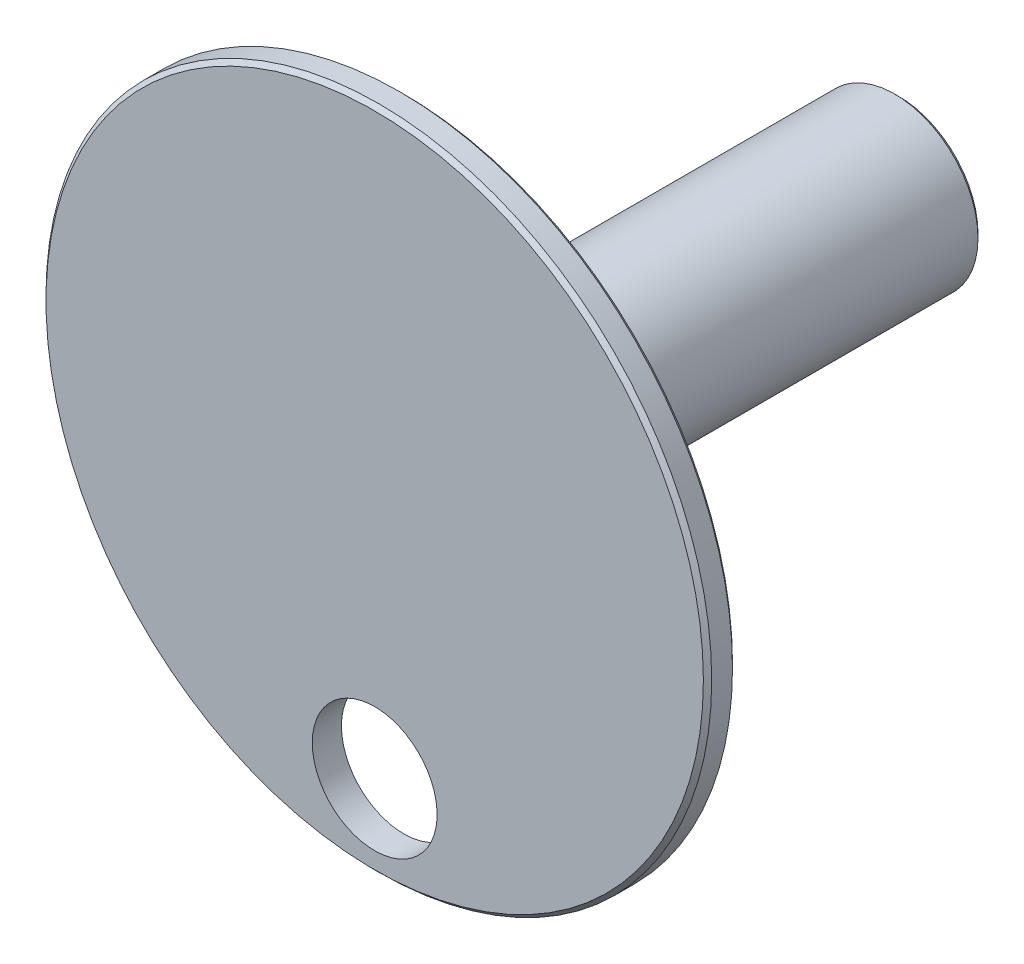
SolidWorks part; units mm, degrees
ref_plane "Front Plane" through (0, 0, 0) normal (0, 0, 1) x (1, 0, 0)
ref_plane "Top Plane" through (0, 0, 0) normal (0, 1, 0) x (1, 0, 0)
ref_plane "Right Plane" through (0, 0, 0) normal (1, 0, 0) x (0, 0, -1)
sketch "Sketch2" plane through (0, 0, 0) normal (0, 0, 1) x (1, 0, 0)
  circle A0 centre (0, 0) radius 2
  dimension "D1" = 4
extrude "Boss-Extrude1" add sketch "Sketch2" along normal blind 11.6
sketch "Sketch3" plane through (0, 0, 11.6) normal (0, 0, 1) x (1, 0, 0)
  circle A0 centre (0, 0) radius 4
  dimension "D1" = 8
extrude "Boss-Extrude2" add sketch "Sketch3" along normal blind 0.3
sketch "Sketch4" plane through (0, 0, 11.9) normal (0, 0, 1) x (1, 0, 0)
  circle A0 centre (0, 0) radius 8
  dimension "D1" = 16
extrude "Boss-Extrude3" add sketch "Sketch4" along normal blind 0.7
sketch "Sketch5" plane through (0, 0, 0) normal (0, 0, -1) x (-1, 0, 0)
  circle A0 centre (0, 0) radius 1.5
  dimension "D1" = 3
extrude "Cut-Extrude1" cut sketch "Sketch5" against normal blind 8.5
sketch "Sketch7" plane through (0, 0, 11.9) normal (0, 0, -1) x (-1, 0, 0)
  line L0 (0, 0) -> (0, -8) construction
  line L1 (0, -8) -> (0, -4) construction
  circle A0 centre (0, 0) radius 8 construction
  circle A1 centre (0, -6) radius 1.5
  dimension "D1" = 3
extrude "Cut-Extrude2" cut sketch "Sketch7" against normal through all
chamfer "Chamfer1" distance 0.1 angle 45 3 edges at (2, 0, 0) (8, 0, 11.9) (8, 0, 12.6)
